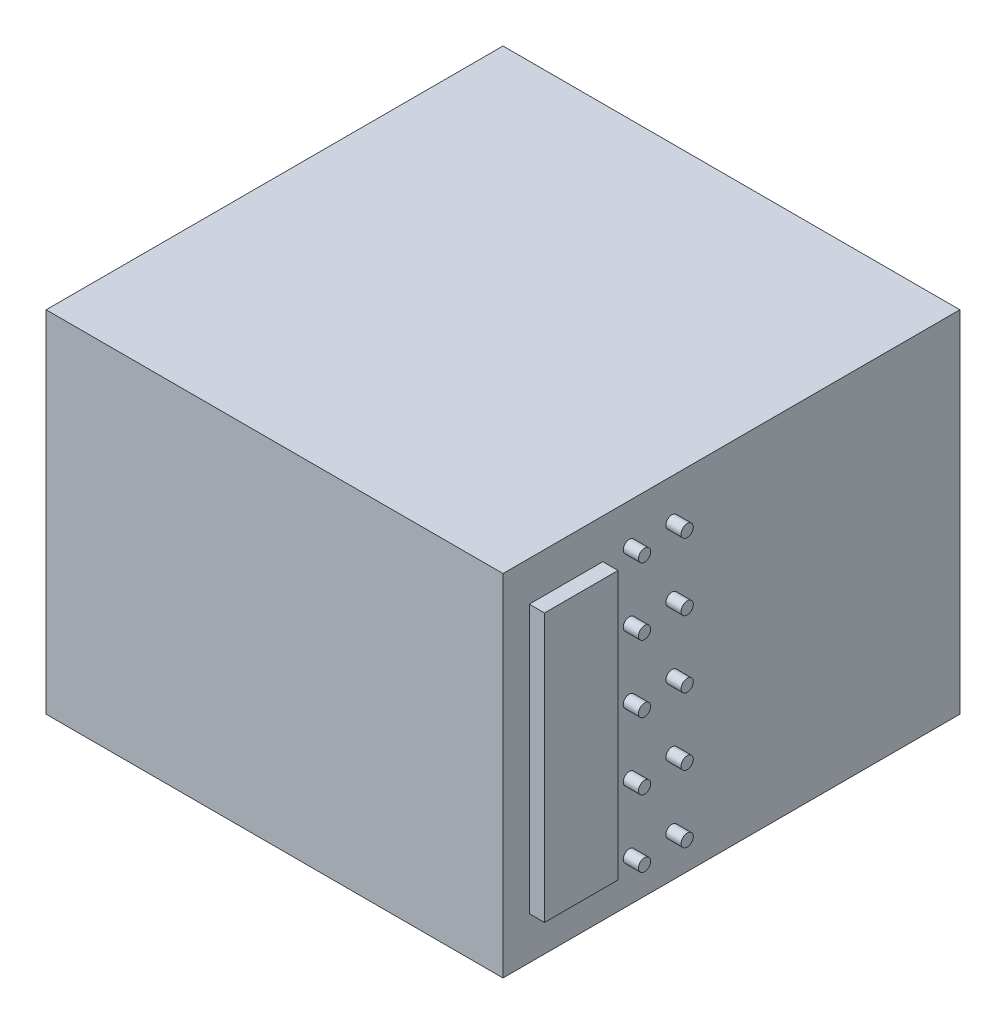
SolidWorks part; units mm, degrees
ref_plane "Front Plane" through (0, 0, 0) normal (0, 0, 1) x (1, 0, 0)
ref_plane "Top Plane" through (0, 0, 0) normal (0, 1, 0) x (1, 0, 0)
ref_plane "Right Plane" through (0, 0, 0) normal (1, 0, 0) x (0, 0, -1)
sketch "Sketch1" plane through (0, 0, 0) normal (0, 0, 1) x (1, 0, 0)
  line L1 (5905.6604, 9363.2075) -> (7405.6604, 9363.2075)
  line L2 (5905.6604, 9363.2075) -> (5905.6604, 8213.2075)
  line L3 (5905.6604, 8213.2075) -> (7405.6604, 8213.2075)
  line L4 (7405.6604, 9363.2075) -> (7405.6604, 8213.2075)
  dimension "D1" = 1500
  dimension "D2" = 1150
extrude "Boss-Extrude1" add sketch "Sketch1" along normal blind 1500
sketch "Sketch2" plane through (7405.6604, 0, 0) normal (1, 0, 0) x (0, 0, -1)
  line L1 (-1413.7341, 8353.0744) -> (-1172.3234, 8353.0744)
  line L2 (-1413.7341, 8353.0744) -> (-1413.7341, 9233.0744)
  line L3 (-1413.7341, 9233.0744) -> (-1172.3234, 9233.0744)
  line L4 (-1172.3234, 8353.0744) -> (-1172.3234, 9233.0744)
  circle A0 centre (-1085.2345, 8353.0744) radius 20
  circle A2 centre (-945.2345, 8353.0744) radius 20
  circle A3 centre (-945.2345, 8573.0744) radius 20
  circle A4 centre (-945.2345, 8793.0744) radius 20
  circle A5 centre (-945.2345, 9013.0744) radius 20
  circle A6 centre (-945.2345, 9233.0744) radius 20
  circle A7 centre (-1085.2345, 8573.0744) radius 20
  circle A8 centre (-1085.2345, 8793.0744) radius 20
  circle A9 centre (-1085.2345, 9013.0744) radius 20
  circle A10 centre (-1085.2345, 9233.0744) radius 20
  dimension "D1" = 2
  dimension "D2" = 5
extrude "Boss-Extrude2" add sketch "Sketch2" along normal blind 50
